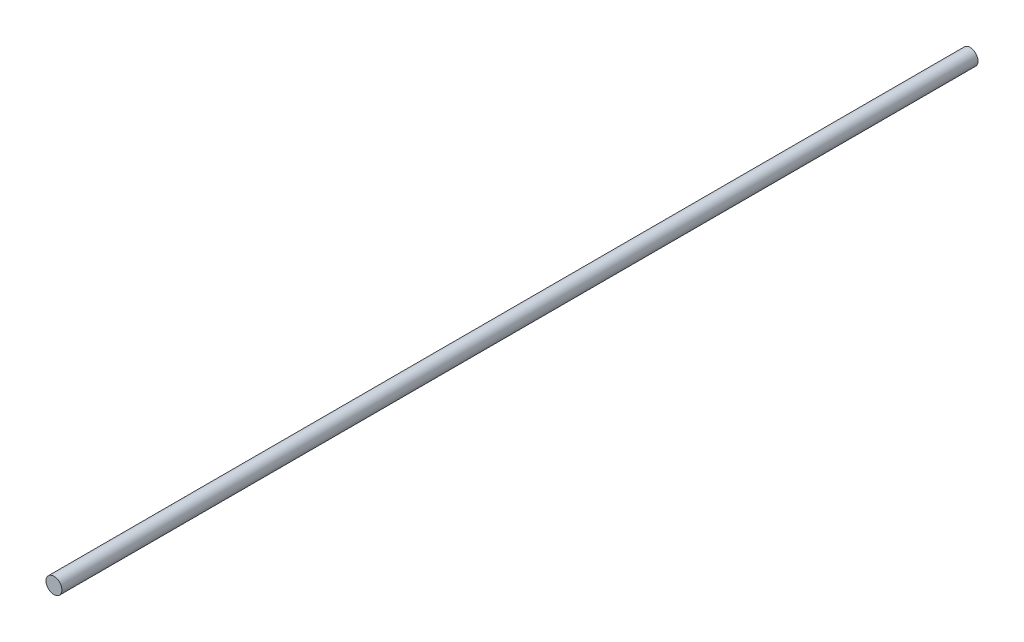
SolidWorks part; units mm, degrees
ref_plane "Front" through (0, 0, 0) normal (0, 0, 1) x (1, 0, 0)
ref_plane "Top" through (0, 0, 0) normal (0, 1, 0) x (1, 0, 0)
ref_plane "Right" through (0, 0, 0) normal (1, 0, 0) x (0, 0, -1)
sketch "Esquisse1" plane through (0, 0, 0) normal (0, 0, 1) x (1, 0, 0)
  circle A0 centre (0, 0) radius 4
  dimension "D1" = 8
extrude "Boss.-Extru.1" add sketch "Esquisse1" along normal blind 461
